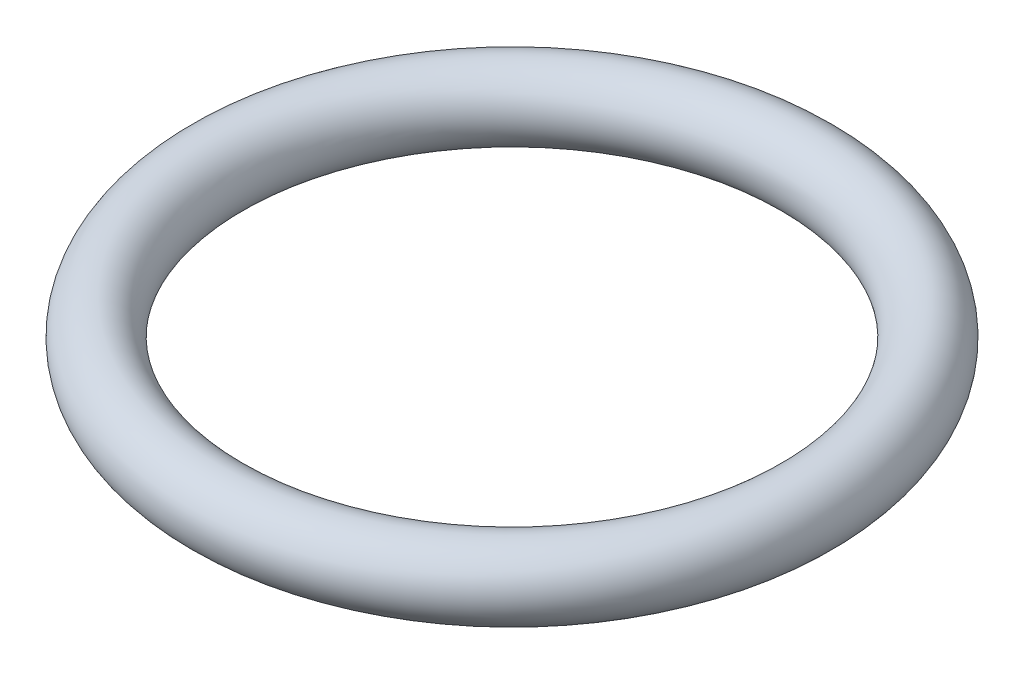
SolidWorks part; units mm, degrees
ref_plane "前视基准面" through (0, 0, 0) normal (0, 0, 1) x (1, 0, 0)
ref_plane "上视基准面" through (0, 0, 0) normal (0, 1, 0) x (1, 0, 0)
ref_plane "右视基准面" through (0, 0, 0) normal (1, 0, 0) x (0, 0, -1)
sketch "草图1" plane through (0, 0, 0) normal (0, 1, 0) x (1, 0, 0)
  circle A0 centre (0, 0) radius 11
  dimension "D1" = 22
sweep "扫描1" add path "草图1" circular profile diameter 2.65 parameters "D3"=2.65
sketch "草图14" plane through (0, 0, 0) normal (0, 0, 1) x (1, 0, 0)
  line L0 (0, 0) -> (0, 9.8948)
